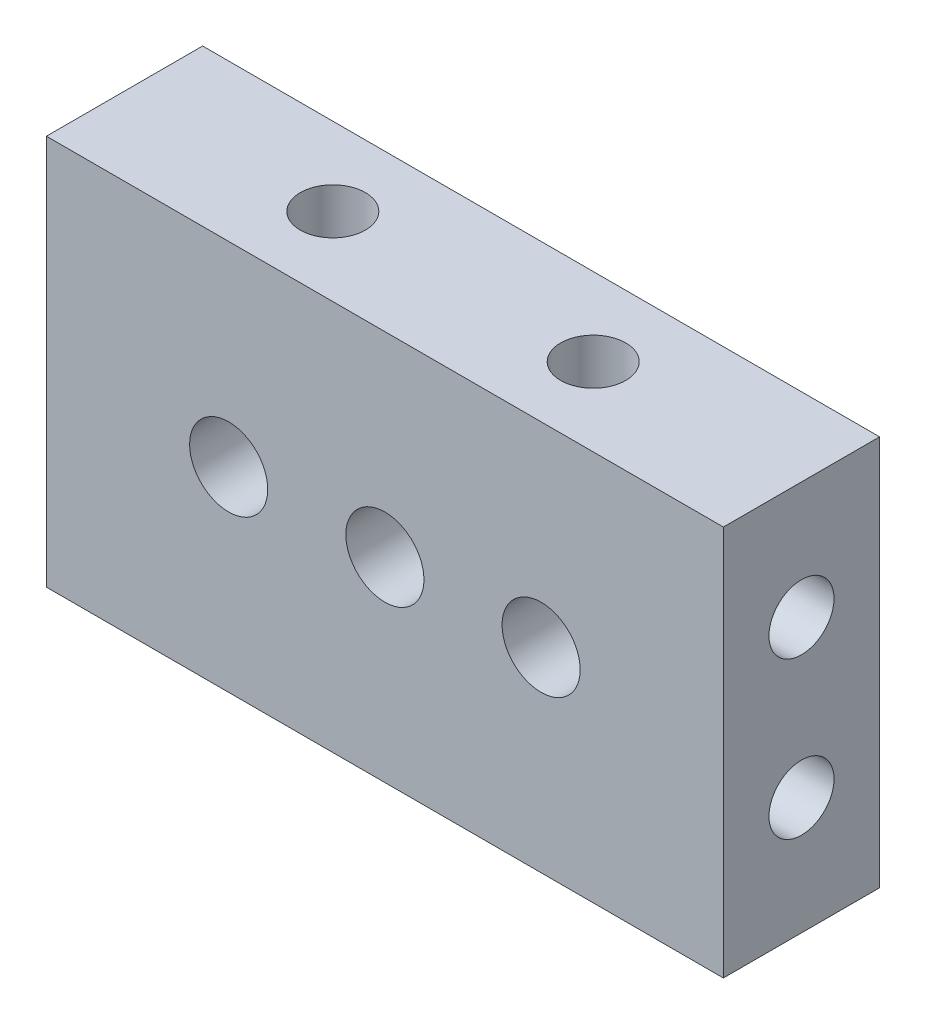
SolidWorks part; units mm, degrees
material "6063-T1"
ref_plane "前视基准面" through (0, 0, 0) normal (0, 0, 1) x (1, 0, 0)
ref_plane "上视基准面" through (0, 0, 0) normal (0, 1, 0) x (1, 0, 0)
ref_plane "右视基准面" through (0, 0, 0) normal (1, 0, 0) x (0, 0, -1)
sketch "草图1" plane through (0, 0, 0) normal (0, 0, 1) x (1, 0, 0)
  line L0 (0, 10.6463) -> (0, -8.7034) construction
  line L2 (-13, -7.5) -> (13, -7.5)
  line L3 (-13, -7.5) -> (-13, 7.5)
  line L4 (-13, 7.5) -> (13, 7.5)
  line L5 (13, -7.5) -> (13, 7.5)
  line L6 (-13, -7.5) -> (13, 7.5) construction
  line L7 (-13, 7.5) -> (13, -7.5) construction
  point P3 (0, 0)
  dimension "D1" = 26
  dimension "D2" = 15
extrude "凸台-拉伸1" add sketch "草图1" along normal blind 5
sketch "草图2" plane through (0, 0, 5) normal (0, 0, 1) x (1, 0, 0)
  line L0 (0, 11.4812) -> (0, -11.5028) construction
  line L5 (13, -7.5) -> (13, 7.5)
  line L6 (13, 7.5) -> (-13, 7.5)
  line L7 (-13, 7.5) -> (-13, -7.5)
  line L8 (-13, -7.5) -> (13, -7.5)
  line L9 (13, -7.5) -> (13, 7.5)
  line L10 (13, 7.5) -> (-13, 7.5)
  line L11 (-13, 7.5) -> (-13, -7.5)
  line L12 (-13, -7.5) -> (13, -7.5)
  dimension "D1" = 0
extrude "凸台-拉伸2" add sketch "草图2" along normal blind 1
sketch "草图3" plane through (-13, 0, 0) normal (-1, 0, 0) x (0, 0, 1)
  line L0 (8.9091, 0) -> (-5.7088, 0) construction
  line L1 (3, 10.2021) -> (3, -13.0987) construction
  line L2 (0, 7.5) -> (0, -7.5) construction
  circle A0 centre (3, 3) radius 1.5
  circle A2 centre (3, -3) radius 1.5
  dimension "D1" = 3
  dimension "D4" = 3
  dimension "D2" = 3
  dimension "D3" = 3
hole_wizard "M3 螺纹孔1" positions "3D草图1" profile "草图4" tap size "M3" standard "GB"
sketch3d "3D草图1"
  point P0 (-13, -3, 3)
  point P6 (-13, 3, 3)
sketch "草图4" plane through (-13, -3, 3) normal (0, 1, 0) x (0, 0, 1)
  line L0 (0, 0) -> (0, 5.7511)
  line L1 (0, 5.7511) -> (1.25, 5)
  line L2 (1.25, 5) -> (1.25, 0)
  line L5 (1.25, 0) -> (0, 0)
  line L10 (0, 5.7511) -> (-1.25, 5) construction
  line L11 (0, -6.35) -> (0, 107.95) construction
  dimension "螺纹孔钻头直径" = 2.5
  dimension "螺纹孔钻头深度" = 5
  dimension "导头角度" = 118
cosmetic thread "孔螺蚊线1" parameters "D1"=4.5, "D2"=3
cosmetic thread "孔螺蚊线3" parameters "D1"=4.5, "D2"=3
mirror "镜向1" about plane through (0, 0, 0) normal (1, 0, 0) of "M3 螺纹孔1"
sketch "草图5" plane through (0, 0, 0) normal (0, 0, -1) x (-1, 0, 0)
  line L0 (20.4871, 0) -> (-26.3319, 0) construction
  circle A0 centre (6, 0) radius 1.5
  circle A1 centre (0, 0) radius 1.5
  circle A2 centre (-6, 0) radius 1.5
  dimension "D1" = 3
  dimension "D2" = 6
  dimension "D3" = 6
extrude "切除-拉伸1" cut sketch "草图5" against normal blind 7
sketch "草图6" plane through (0, 7.5, 0) normal (0, 1, 0) x (1, 0, 0)
  line L0 (14.7385, -3) -> (-15.8006, -3) construction
  line L1 (13, -6) -> (-13, -6) construction
  line L2 (0, 3.998) -> (0, -10.3713) construction
  circle A0 centre (5, -3) radius 1.5
  circle A1 centre (-5, -3) radius 1.5
  dimension "D2" = 3
  dimension "D1" = 3
  dimension "D3" = 5
  dimension "D4" = 5
hole_wizard "M3 螺纹孔2" positions "3D草图2" profile "草图7" tap size "M3" standard "GB"
sketch3d "3D草图2"
  point P0 (5, 7.5, 3)
  point P3 (-5, 7.5, 3)
sketch "草图7" plane through (5, 7.5, 3) normal (1, 0, 0) x (0, 0, 1)
  line L0 (0, 0) -> (0, 7.7511)
  line L1 (0, 7.7511) -> (1.25, 7)
  line L2 (1.25, 7) -> (1.25, 0)
  line L5 (1.25, 0) -> (0, 0)
  line L10 (0, 7.7511) -> (-1.25, 7) construction
  line L11 (0, -6.35) -> (0, 107.95) construction
  dimension "螺纹孔钻头直径" = 2.5
  dimension "螺纹孔钻头深度" = 7
  dimension "导头角度" = 118
cosmetic thread "孔螺蚊线4" parameters "D1"=4.5, "D2"=3
cosmetic thread "孔螺蚊线5" parameters "D1"=4.5, "D2"=3
